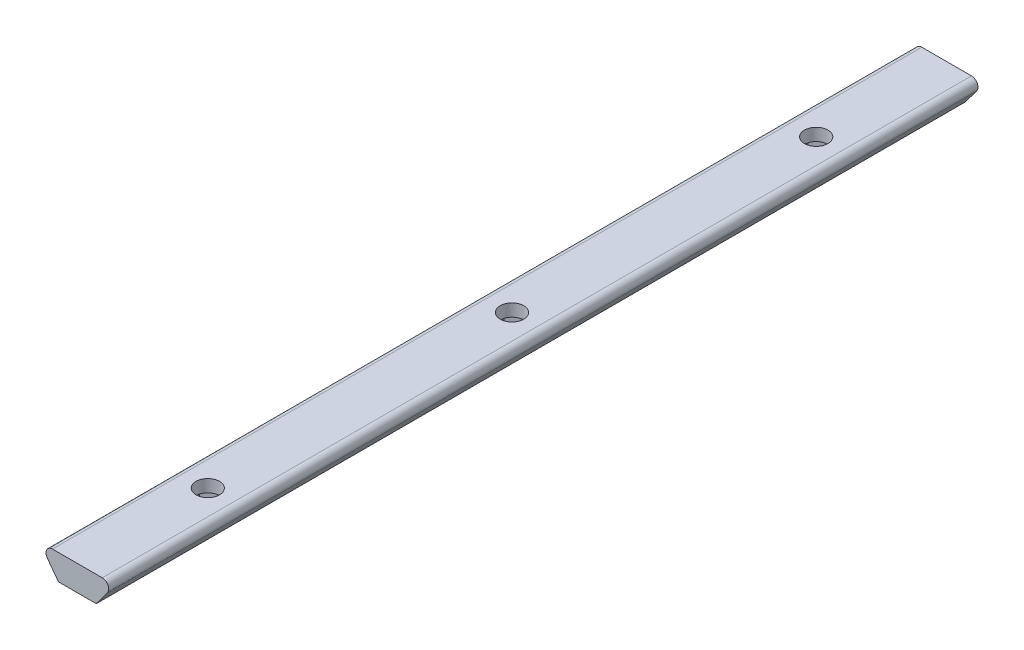
SolidWorks part; units mm, degrees
ref_plane "Front Plane" through (0, 0, 0) normal (0, 0, 1) x (1, 0, 0)
ref_plane "Top Plane" through (0, 0, 0) normal (0, 1, 0) x (1, 0, 0)
ref_plane "Right Plane" through (0, 0, 0) normal (1, 0, 0) x (0, 0, -1)
sketch "Sketch1" plane through (0, 0, 0) normal (0, 0, 1) x (1, 0, 0)
  line L0 (0, 0) -> (5.8, 0)
  line L1 (-2.9, 3.9) -> (8.7, 3.9)
  line L2 (0, 0) -> (-2.9, 3.9)
  line L3 (5.8, 0) -> (8.7, 3.9)
  dimension "D1" = 11.6
  dimension "D2" = 3.9
  dimension "D3" = 5.8
  dimension "D4" = 2.9
extrude "Boss-Extrude1" add sketch "Sketch1" along normal blind 133.3
fillet "Fillet1" radius 1 2 edges at (-2.9, 3.9, 66.65) (8.7, 3.9, 66.65)
sketch "Sketch2" plane through (0, 0, 0) normal (0, -1, 0) x (1, 0, 0)
  line L0 (2.9, 133.3) -> (2.9, 113.3) construction
  line L1 (0, 133.3) -> (5.8, 133.3) construction
  circle A0 centre (2.9, 113.3) radius 1.8
  dimension "D2" = 3.6
  dimension "D1" = 20
extrude "Cut-Extrude1" cut sketch "Sketch2" against normal blind 200
sketch "Sketch3" plane through (0, 0, 0) normal (0, -1, 0) x (1, 0, 0)
  line L1 (5.7876, 111.6043) -> (5.8123, 114.9528)
  line L2 (5.8123, 114.9528) -> (2.9247, 116.6485)
  line L3 (2.9247, 116.6485) -> (0.0124, 114.9957)
  line L4 (0.0124, 114.9957) -> (-0.0123, 111.6472)
  line L5 (-0.0123, 111.6472) -> (2.8753, 109.9515)
  line L6 (2.8753, 109.9515) -> (5.7876, 111.6043)
  circle A0 centre (2.9, 113.3) radius 2.9 construction
  dimension "D1" = 5.8
extrude "Cut-Extrude2" cut sketch "Sketch3" against normal blind 2
pattern_linear "LPattern1" count 3 spacing 46.65 along (0, 0, -1) of "Cut-Extrude1", "Cut-Extrude2"
